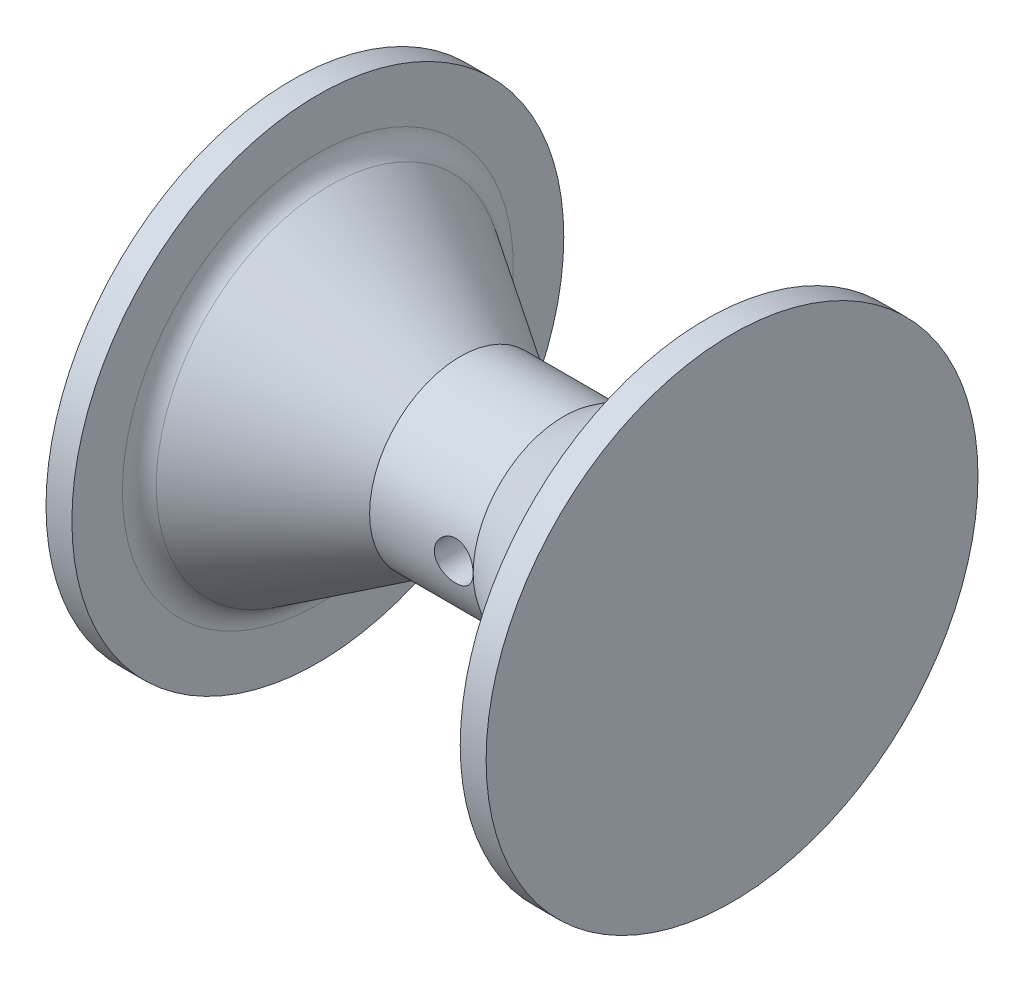
SolidWorks part; units mm, degrees
ref_plane "Front Plane" through (0, 0, 0) normal (0, 0, 1) x (1, 0, 0)
ref_plane "Top Plane" through (0, 0, 0) normal (0, 1, 0) x (1, 0, 0)
ref_plane "Right Plane" through (0, 0, 0) normal (1, 0, 0) x (0, 0, -1)
sketch "Sketch2" plane through (0, 0, 0) normal (0, 0, 1) x (1, 0, 0)
  line L0 (0, 0) -> (23.9161, 0) construction
  line L2 (0, 0) -> (0, 13.1643) construction
  line L3 (15, 14) -> (15, 19)
  line L4 (15, 19) -> (17, 19)
  line L5 (17, 19) -> (17, 0)
  line L6 (-4, 7) -> (4, 7)
  line L7 (4, 7) -> (15, 14)
  line L8 (-4, 7) -> (-15, 14)
  line L9 (-17, 19) -> (-17, 0)
  line L10 (-15, 19) -> (-17, 19)
  line L11 (-15, 14) -> (-15, 19)
  line L12 (-17, 0) -> (17, 0)
  dimension "D1" = 17
  dimension "D2" = 19
  dimension "D3" = 5
  dimension "D4" = 4
  dimension "D5" = 2
  dimension "D6" = 7
revolve "Revolve1" add sketch "Sketch2" angle 360 about L0
sketch "Sketch3" plane through (-17, 0, 0) normal (-1, 0, 0) x (0, 0, 1)
  line L0 (2.9, 1.5748) -> (2.9, -1.5748)
  arc A0 (2.9, 1.5748) -> (2.9, -1.5748) centre (0, 0) ccw
extrude "motor shaft" cut sketch "Sketch3" against normal blind 13
sketch "Sketch4" plane through (0, 0, 0) normal (0, 0, 1) x (1, 0, 0)
  line L0 (4, 7) -> (4, -7) construction
  circle A0 centre (0, 0) radius 1.5 construction
  circle A1 centre (2.5, 0) radius 1.5
  circle A2 centre (-5, 0) radius 1.5 construction
  point P4 (2.8047, 0)
  dimension "D1" = 3
  dimension "D2" = 2
  dimension "D3" = 2
extrude "string holes" cut sketch "Sketch4" against normal mid plane 35
fillet "Fillet1" radius 2 2 edges at (-15, 0, 14) (15, 0, 14)
